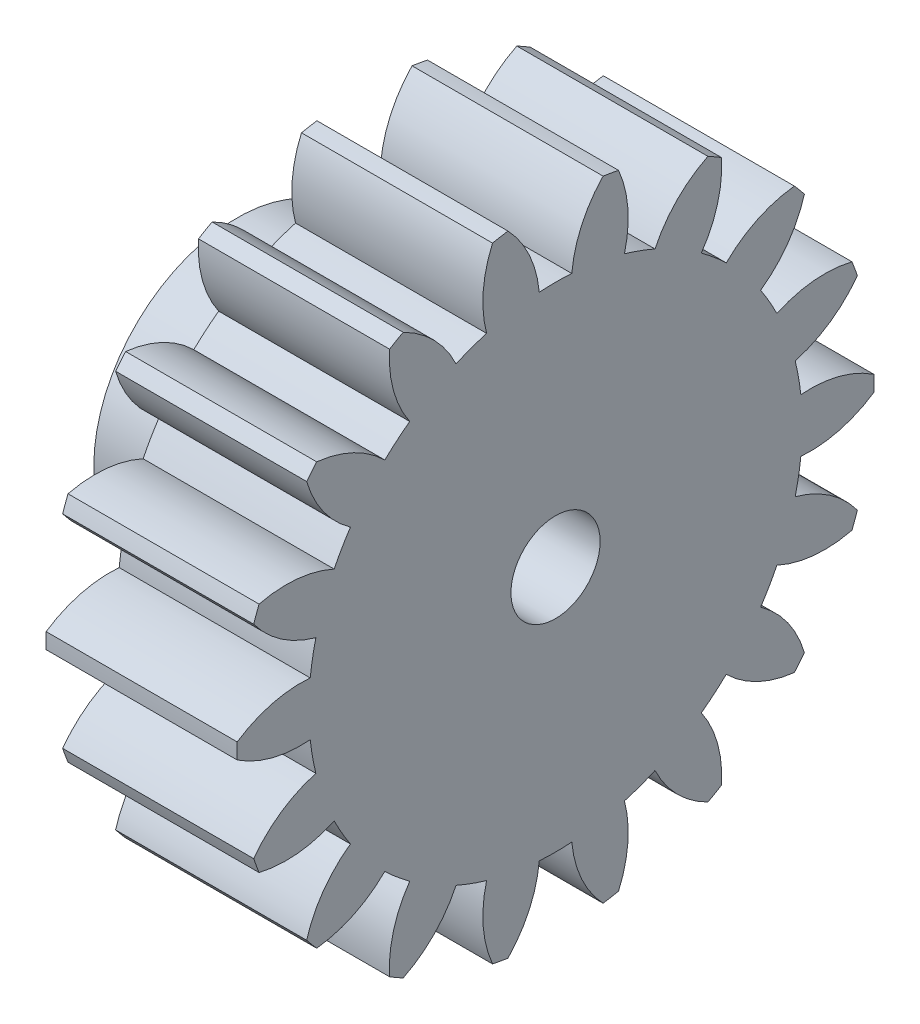
SolidWorks part; units mm, degrees
ref_plane "Plane1" through (0, 0, 0) normal (0, 0, 1) x (1, 0, 0)
ref_plane "Plane2" through (0, 0, 0) normal (0, 1, 0) x (1, 0, 0)
ref_plane "Plane3" through (0, 0, 0) normal (1, 0, 0) x (0, 0, -1)
other "Configuration Table"
sketch "HoldingSke" plane through (0, 0, 0) normal (0, 1, 0) x (1, 0, 0)
  line L0 (0, 0) -> (0.9511, -0.309)
  line L1 (-15, 0) -> (100, 0) construction
  line L2 (0, 0) -> (-2.1039, 2.3779)
  line L3 (0, 0) -> (-11.863, 4.5341)
  line L4 (0, 0) -> (8.2133, 2.6687)
  line L5 (0, 0) -> (-46.8476, -17.4728)
  line L6 (0, 0) -> (-4.9738, -3.3558)
  line L7 (-2.1039, 2.3779) -> (8.6586, 51.2059)
  line L8 (-76.2, 54.61) -> (-76.1, 54.61)
  line L9 (-71.009, 38.7566) -> (-53.1078, 45.2721)
  line L10 (-76.2, 71.12) -> (104.1128, 71.12)
  line L11 (0, 0) -> (-6, 0)
  line L12 (-76.2, 101.6) -> (-76.162, 101.6)
  line L13 (24.9733, 27.94) -> (52.9518, 28.4284)
  line L14 (24.9733, 27.94) -> (24.9743, 27.94)
  line L15 (24.9733, 27.94) -> (100.4006, 29.5858)
  line L16 (-63.627, -1) -> (-12.827, -1)
  circle A0 centre (0, 0) radius 0.5
  circle A1 centre (0, 0) radius 7.749
  circle A2 centre (0, 0) radius 37.5
  circle A3 centre (0, 0) radius 0.5
  dimension "MHD" = 15.498
  dimension "Hub_dia" = 75
  dimension "Bore" = 1
  dimension "MBD" = 1
  dimension "Num_teeth" = 18
  dimension "Pitch" = 1
  dimension "Overall_len" = 50
  dimension "Show_teeth" = 18
  dimension "Thickness" = 6
  dimension "OAL" = 50.0001
  dimension "T_dim" = 0.1
  dimension "Ap" = 20
  dimension "H" = 19.05
  dimension "Pitch_radius" = 180.3128
  dimension "Width" = 6
  dimension "Backlash" = 0.038
  dimension "Addendum_fac" = 1
  dimension "Dedendum_fac" = 1.25
  dimension "Clearance_fac" = 0.25
  dimension "Dedendum_add" = 0.001
  dimension "Module" = 1
sketch "BasProSke" plane through (0, 0, 0) normal (0, 1, 0) x (1, 0, 0)
  line L0 (-10, 0) -> (60, 0) construction
  line L1 (0, 0) -> (0, 10)
  line L2 (0, 0) -> (6, 0)
  line L3 (6, 0) -> (6, 10)
  line L4 (6, 10) -> (0, 10)
  dimension "Thickness" = 6
  dimension "Diameter" = 20
revolve "Base-Revolve" add sketch "BasProSke" angle 360 about L0
sketch "TooCutSke" plane through (0, 0, 0) normal (1, 0, 0) x (0, 0, -1)
  line L1 (0, 0) -> (0, 107) construction
  line L2 (0, 0) -> (-0.8509, 8.9597) construction
  line L3 (0, 0) -> (-3.1157, 17.6701) construction
  line L4 (-0.8509, 8.9597) -> (-1.5579, 8.835) construction
  arc A0 (0.5106, 7.7322) -> (-0.5106, 7.7322) centre (0, 0) ccw
  arc A1 (1.5152, 9.9102) -> (-1.5152, 9.9102) centre (0, 0) ccw
  circle A2 centre (0, 0) radius 9 construction
  circle A3 centre (0, 0) radius 8.4572 construction
  arc A4 (-0.5106, 7.7322) -> (-1.5152, 9.9102) centre (-4.0952, 7.3996) ccw
  arc A5 (1.5152, 9.9102) -> (0.5106, 7.7322) centre (4.0952, 7.3996) ccw
  dimension "Root_dia" = 15.498
  dimension "Overcut_dia" = 20.0508
  dimension "Pitch_dia" = 18
  dimension "Base_dia" = 16.9145
  dimension "Flank_rad" = 3.6
  dimension "Half_ang" = 10
  dimension "Half_CT" = 0.7179
extrude "ToothCut" cut sketch "TooCutSke" along normal through all
fillet "Breaks" [suppressed] radius 0.02
fillet "RootFillets" [suppressed] radius 0.251
pattern_circular "TeethCuts" count 18 every 20 about axis through (-10, 0, 0) along (1, 0, 0) of "ToothCut", "RootFillets", "Breaks"
sketch "HubNeaOneSke" plane through (0, 0, 0) normal (-1, 0, 0) x (0, 0, 1)
  circle A0 centre (0, 0) radius 7.749
  dimension "Diameter" = 15.498
extrude "HubNearOne" [suppressed] add sketch "HubNeaOneSke" along normal blind 44.0001
sketch "HubNeaBotSke" plane through (0, 0, 0) normal (-1, 0, 0) x (0, 0, 1)
  circle A0 centre (0, 0) radius 7.749
  dimension "Diameter" = 15.498
extrude "HubNearBoth" [suppressed] add sketch "HubNeaBotSke" along normal blind 22
ref_plane "FarPln" through (6, 0, 0) normal (1, 0, 0) x (0, 0, -1)
sketch "HubFarSke" plane through (6, 0, 0) normal (1, 0, 0) x (0, 0, -1)
  circle A0 centre (0, 0) radius 7.749
  dimension "Diameter" = 15.498
extrude "HubFar" [suppressed] add sketch "HubFarSke" along normal blind 22
sketch "BorSke" plane through (0, 0, 0) normal (1, 0, 0) x (0, 0, -1)
  circle A0 centre (0, 0) radius 0.5
  dimension "Diameter" = 1
extrude "Bore" cut sketch "BorSke" along normal mid plane 100.0001
sketch "KeySke" plane through (0, 0, 0) normal (1, 0, 0) x (0, 0, -1)
  line L0 (-0.05, 0) -> (-0.05, 0.6)
  line L1 (-0.05, 0.6) -> (0.05, 0.6)
  line L2 (0.05, 0.6) -> (0.05, 0)
  line L3 (0, 0) -> (0, 34) construction
  line L4 (-0.05, 0) -> (0.05, 0)
  dimension "Offset" = 0.6
  dimension "Width" = 0.1
extrude "Keyway" [suppressed] cut sketch "KeySke" along normal mid plane 100.0001
pattern_circular "Keyway2" [suppressed] count 2 every 90 about axis through (-10, 0, 0) along (1, 0, 0)
sketch "Sketch1" plane through (0, 0, 0) normal (-1, 0, 0) x (0, 0, 1)
  circle A0 centre (0, 0) radius 4.5
  dimension "D1" = 9
sketch "Sketch3" plane through (6, 0, 0) normal (1, 0, 0) x (0, 0, -1)
  circle A0 centre (0, 0) radius 2.3
extrude "Boss-Extrude3" add sketch "Sketch3" against normal up to surface (6 mm away) up to face at (0, 0, -0.5)
extrude "Boss-Extrude4" add sketch "Sketch1" along normal blind 4
sketch "Sketch4" plane through (-4, 0, 0) normal (-1, 0, 0) x (0, 0, 1)
  circle A0 centre (0, 0) radius 2.5
  dimension "D1" = 5
extrude "Cut-Extrude1" cut sketch "Sketch4" against normal up to surface (4 mm away) up to face at (0, 0, -4.5)
sketch "Sketch5" plane through (6, 0, 0) normal (1, 0, 0) x (0, 0, -1)
  circle A0 centre (0, 0) radius 1.4
  dimension "D1" = 2.8
extrude "Cut-Extrude2" cut sketch "Sketch5" against normal up to surface (6 mm away) up to face at (0, 0, -4.5)
equation "' \"Module@HoldingSke\" = 6.35"
equation "' \"Num_teeth@HoldingSke\" = 12"
equation "' \"Ap@HoldingSke\" =  20"
equation "' \"Ap@HoldingSke\" = 20"
equation "' \"Width@HoldingSke\" = 0.5 * 25.4"
equation "' \"Hub_dia@HoldingSke\"= 1 * 25.4"
equation "' \"Hub_dia@HoldingSke\" = 1 * 25.4"
equation "' \"Overall_len@HoldingSke\" = 1.0 * 25.4"
equation "' \"Bore@HoldingSke\" = 0.75 * 25.4"
equation "' \"T_dim@HoldingSke\" = 0.1 * 25.4"
equation "' \"Width@KeySke\" = 0.25 * 25.4"
equation "' \"Show_teeth@HoldingSke\" = 13"
equation "' \"Backlash@HoldingSke\" = 0.009 * 25.4"
equation "' \"Addendum_fac@HoldingSke\" = 1.0"
equation "' \"Dedendum_fac@HoldingSke\" = 1.25"
equation "' \"Dedendum_add@HoldingSke\" = 0.00005 * 25.4"
equation "' \"Clearance_fac@HoldingSke\" = 0.25"
equation "\"Pitch@HoldingSke\" = 1 / \"Module@HoldingSke\""
equation "\"Overcut_dia@TooCutSke\" = (\"Num_teeth@HoldingSke\" + 2 * \"Addendum_fac@HoldingSke\") / \"Pitch@HoldingSke\" + 0.002 * 25.4"
equation "\"Pitch_dia@TooCutSke\" = \"Num_teeth@HoldingSke\" / \"Pitch@HoldingSke\""
equation "\"Base_dia@TooCutSke\" = \"Num_teeth@HoldingSke\" / \"Pitch@HoldingSke\" * cos((\"Ap@HoldingSke\"  * 3.14159265 / 180))"
equation "\"Root_dia@TooCutSke\" = (\"Num_teeth@HoldingSke\" + 2) / \"Pitch@HoldingSke\" - 2 * (\"Addendum_fac@HoldingSke\" + \"Dedendum_fac@HoldingSke\") / \"Pitch@HoldingSke\" - \"Dedendum_add@HoldingSke\" * 2"
equation "\"Half_ang@TooCutSke\" = 180 / \"Num_teeth@HoldingSke\""
equation "\"Half_CT@TooCutSke\" = \"Num_teeth@HoldingSke\" / \"Pitch@HoldingSke\" * sin((3.14159265 / 2 / \"Num_teeth@HoldingSke\")) / 2 - 7 * \"Backlash@HoldingSke\" / 4"
equation "\"Flank_rad@TooCutSke\" = \"Num_teeth@HoldingSke\" / \"Pitch@HoldingSke\" / 5"
equation "\"Radius@RootFillets\" = \"Clearance_fac@HoldingSke\" / \"Pitch@HoldingSke\" + \"Dedendum_add@HoldingSke\""
equation "\"Break_rad@Breaks\" = 0.02 / \"Pitch@HoldingSke\""
equation "\"Thickness@HoldingSke\" = \"Width@HoldingSke\""
equation "\"OAL@HoldingSke\" = \"Thickness@HoldingSke\""
equation "\"MHD@HoldingSke\" = (\"Num_teeth@HoldingSke\" + 2) / \"Pitch@HoldingSke\" - 2 * (\"Addendum_fac@HoldingSke\" + \"Dedendum_fac@HoldingSke\")  / \"Pitch@HoldingSke\" - \"Dedendum_add@HoldingSke\" * 2"
equation "\"MBD@HoldingSke\" = (\"Num_teeth@HoldingSke\" + 2) / \"Pitch@HoldingSke\" - 2 * (\"Addendum_fac@HoldingSke\" + \"Dedendum_fac@HoldingSke\")  / \"Pitch@HoldingSke\" - \"Dedendum_add@HoldingSke\" * 2 - 0.002 * 25.4"
equation "\"MHD@HoldingSke\" = ((sgn( \"MHD@HoldingSke\" - \"Hub_dia@HoldingSke\" )-1)*( \"MHD@HoldingSke\" - \"Hub_dia@HoldingSke\" ))/-2+ \"Hub_dia@HoldingSke\""
equation "\"MBD@HoldingSke\" = ((sgn( \"MBD@HoldingSke\" - \"Bore@HoldingSke\" )-1)*( \"MBD@HoldingSke\" - \"Bore@HoldingSke\" ))/-2+ \"Bore@HoldingSke\""
equation "\"OAL@HoldingSke\" = ((sgn( \"OAL@HoldingSke\" - \"Overall_len@HoldingSke\" )+1)*( \"OAL@HoldingSke\" - \"Overall_len@HoldingSke\" ))/2 + \"Overall_len@HoldingSke\" + 0.000002 * 25.4"
equation "\"Num_teeth@TeethCuts\" = int( \"Show_teeth@HoldingSke\" ) + 1"
equation "\"Num_teeth@TeethCuts\" = ((sgn( \"Num_teeth@TeethCuts\" - \"Num_teeth@HoldingSke\" )-1)*( \"Num_teeth@TeethCuts\" - \"Num_teeth@HoldingSke\" ))/-2+ \"Num_teeth@HoldingSke\""
equation "\"Num_teeth@TeethCuts\" = ((sgn( \"Num_teeth@TeethCuts\" - 2.0)+1)*( \"Num_teeth@TeethCuts\" - 2.0))/2 +2.0"
equation "\"Angle@TeethCuts\" = 360.0 / \"Num_teeth@HoldingSke\""
equation "\"Diameter@BasProSke\" = (\"Num_teeth@HoldingSke\" + 2 * \"Addendum_fac@HoldingSke\") / \"Pitch@HoldingSke\""
equation "\"Thickness@BasProSke\"  = \"Thickness@HoldingSke\""
equation "' \"Fillet_rad@BasProSke\" =  \"Thickness@HoldingSke\" * 0.05"
equation "' \"Fillet_rad@BasProSke\" = \"Thickness@HoldingSke\" * 0.05"
equation "\"MHD@HoldingSke\" = ((sgn( \"MHD@HoldingSke\" - \"Root_dia@TooCutSke\" )-1)*( \"MHD@HoldingSke\" - \"Root_dia@TooCutSke\" ))/-2+ \"Root_dia@TooCutSke\""
equation "\"Diameter@HubNeaOneSke\" = \"MHD@HoldingSke\""
equation "\"Length@HubNearOne\" = \"OAL@HoldingSke\" - \"Thickness@BasProSke\""
equation "\"Diameter@HubNeaBotSke\" = \"MHD@HoldingSke\""
equation "\"Length@HubNearBoth\" = ( \"OAL@HoldingSke\" - \"Thickness@BasProSke\" ) / 2.0"
equation "\"Thickness@FarPln\" = \"Thickness@BasProSke\""
equation "\"Diameter@HubFarSke\" = \"MHD@HoldingSke\""
equation "\"Length@HubFar\" = ( \"OAL@HoldingSke\" - \"Thickness@BasProSke\" ) / 2.0"
equation "\"Diameter@BorSke\" = \"MBD@HoldingSke\""
equation "\"D1@Bore\" = \"OAL@HoldingSke\" * 2.0"
equation "\"D1@Keyway\" = \"OAL@HoldingSke\" * 2.0"
equation "\"Offset@KeySke\" = \"T_dim@HoldingSke\" + \"MBD@HoldingSke\" / 2.0"
